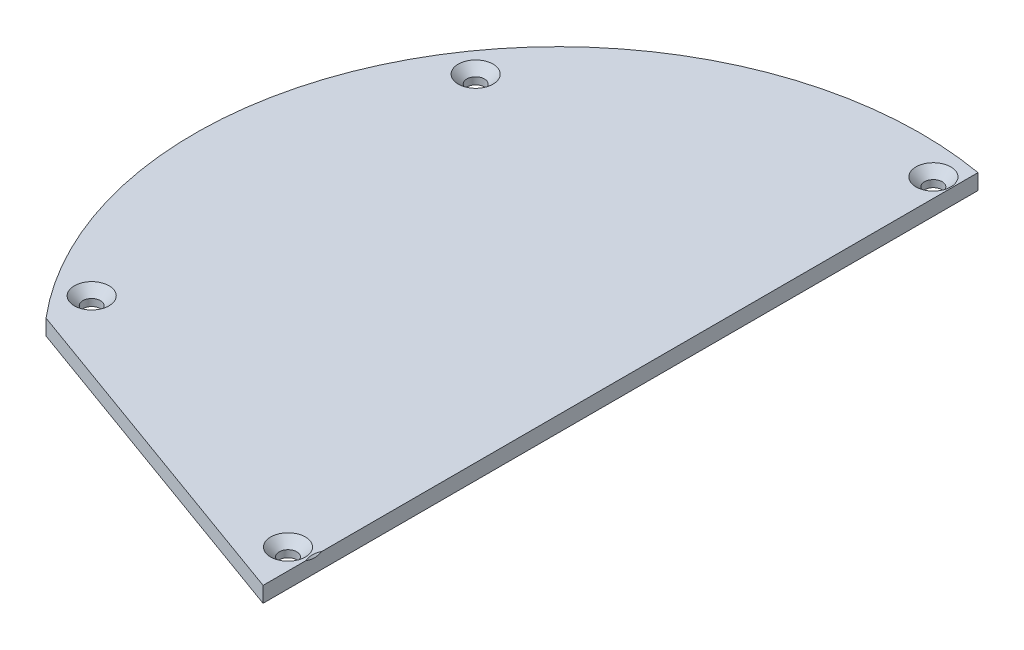
SolidWorks part; units mm, degrees
ref_plane "Front Plane" through (0, 0, 0) normal (0, 0, 1) x (1, 0, 0)
ref_plane "Top Plane" through (0, 0, 0) normal (0, 1, 0) x (1, 0, 0)
ref_plane "Right Plane" through (0, 0, 0) normal (1, 0, 0) x (0, 0, -1)
sketch "Sketch1" plane through (0, 0, 0) normal (0, 1, 0) x (1, 0, 0)
  line L0 (12, 68.9638) -> (12, -68.8024)
  line L1 (12.3, 68.9109) -> (12.3, -68.9109) construction
  line L2 (12, -68.8024) -> (-53.5286, -45.1076)
  line L3 (0, 0) -> (0, 50000) construction
  line L4 (12, -68.8024) -> (12.3, -68.9109) construction
  line L5 (-52.8353, 36.9957) -> (-57.3406, 40.1504) construction
  line L6 (-52.8353, -36.9957) -> (-57.3406, -40.1504) construction
  line L7 (8.4189, 63.9482) -> (9.1368, 69.4011) construction
  arc A0 (12, 68.9638) -> (-53.5286, -45.1076) centre (0, 0) ccw
  arc A1 (12, -68.9638) -> (12, 68.9638) centre (0, 0) ccw construction
  circle A2 centre (8, -60) radius 1.65 construction
  circle A3 centre (-52.8353, -36.9957) radius 1.65 construction
  circle A4 centre (-52.8353, 36.9957) radius 1.65 construction
  circle A5 centre (8.4189, 63.9482) radius 1.65 construction
  point P23 (-52.8353, -36.9957)
  point P24 (8, -60)
  point P25 (8.4189, 63.9482)
  point P26 (-52.8353, 36.9957)
  dimension "D1" = 140
  dimension "D5" = 3.3
  dimension "D2" = 12
  dimension "D3" = 12.3
  dimension "D4" = 70
  dimension "D6" = 8
  dimension "D7" = 60
  dimension "D8" = 5.5
  dimension "D9" = 5.5
  dimension "D10" = 5.5
  dimension "D11" = 7.5
  dimension "D12" = 55
  dimension "D13" = 55
extrude "Boss-Extrude1" add sketch "Sketch1" along normal blind 3
sketch "Sketch2" plane through (0, 3, 0) normal (0, 1, 0) x (1, 0, 0)
  line L0 (12, 68.9638) -> (12, -68.8024)
  line L1 (12.3, 68.9109) -> (12.3, -68.9109) construction
  line L2 (12, -68.8024) -> (-53.5286, -45.1076)
  line L3 (0, 0) -> (0, 50000) construction
  line L4 (12, -68.8024) -> (12.3, -68.9109) construction
  line L5 (-52.8353, 36.9957) -> (-57.3406, 40.1504) construction
  line L6 (-52.8353, -36.9957) -> (-57.3406, -40.1504) construction
  line L7 (8.4189, 63.9482) -> (9.1368, 69.4011) construction
  arc A0 (12, 68.9638) -> (-53.5286, -45.1076) centre (0, 0) ccw
  arc A1 (12, -68.9638) -> (12, 68.9638) centre (0, 0) ccw construction
  circle A2 centre (8, -60) radius 1.65 construction
  circle A3 centre (-52.8353, -36.9957) radius 1.65 construction
  circle A4 centre (-52.8353, 36.9957) radius 1.65 construction
  circle A5 centre (8.4189, 63.9482) radius 1.65 construction
  point P23 (-52.8353, -36.9957)
  point P24 (8, -60)
  point P25 (8.4189, 63.9482)
  point P26 (-52.8353, 36.9957)
  point P28 (15, -59)
  dimension "D1" = 140
  dimension "D5" = 3.3
  dimension "D2" = 12
  dimension "D3" = 12.3
  dimension "D4" = 70
  dimension "D6" = 8
  dimension "D7" = 60
  dimension "D8" = 5.5
  dimension "D9" = 5.5
  dimension "D10" = 5.5
  dimension "D11" = 7.5
  dimension "D12" = 55
  dimension "D13" = 55
hole_wizard "CSK for M3 Flat Head Machine Screw1" positions "Sketch2" profile "Sketch4" countersink size "M3" standard "ANSI Metric" end condition through all
sketch "Sketch4" plane through (15, 3, 59) normal (1, 0, 0) x (0, 0, 1)
  line L0 (0, 0) -> (0, 3)
  line L1 (0, 3) -> (1.7, 3)
  line L2 (1.7, 3) -> (1.7, 1.65)
  line L3 (1.7, 1.65) -> (3.35, 0)
  line L5 (3.35, 0) -> (0, 0)
  line L6 (-1.7, 1.65) -> (-3.35, 0) construction
  line L11 (0, -6.35) -> (0, 107.95) construction
  dimension "Thru Hole Dia." = 3.4
  dimension "Thru Hole Depth" = 3
  dimension "Near C'Sink Dia." = 6.7
  dimension "Near C'Sink Angle" = 90
